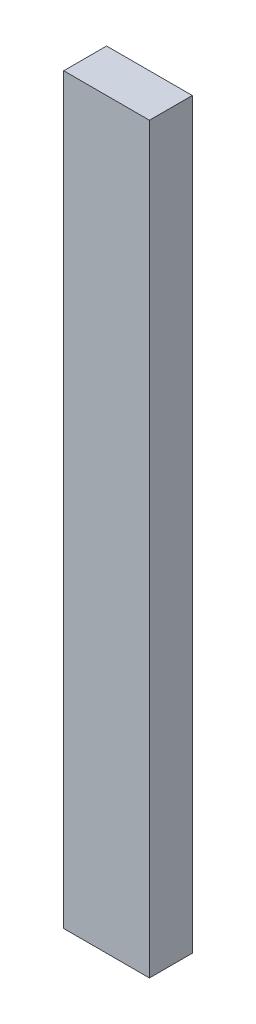
SolidWorks part; units mm, degrees
ref_plane "Front Plane" through (0, 0, 0) normal (0, 0, 1) x (1, 0, 0)
ref_plane "Top Plane" through (0, 0, 0) normal (0, 1, 0) x (1, 0, 0)
ref_plane "Right Plane" through (0, 0, 0) normal (1, 0, 0) x (0, 0, -1)
sketch "Sketch1" plane through (0, 0, 0) normal (0, 1, 0) x (1, 0, 0)
  line L1 (-48.6471, 2.3824) -> (-18.6471, 2.3824)
  line L2 (-48.6471, 2.3824) -> (-48.6471, -12.6176)
  line L3 (-48.6471, -12.6176) -> (-18.6471, -12.6176)
  line L4 (-18.6471, 2.3824) -> (-18.6471, -12.6176)
  dimension "D1" = 30
  dimension "D2" = 15
extrude "Boss-Extrude1" add sketch "Sketch1" along normal blind 260
